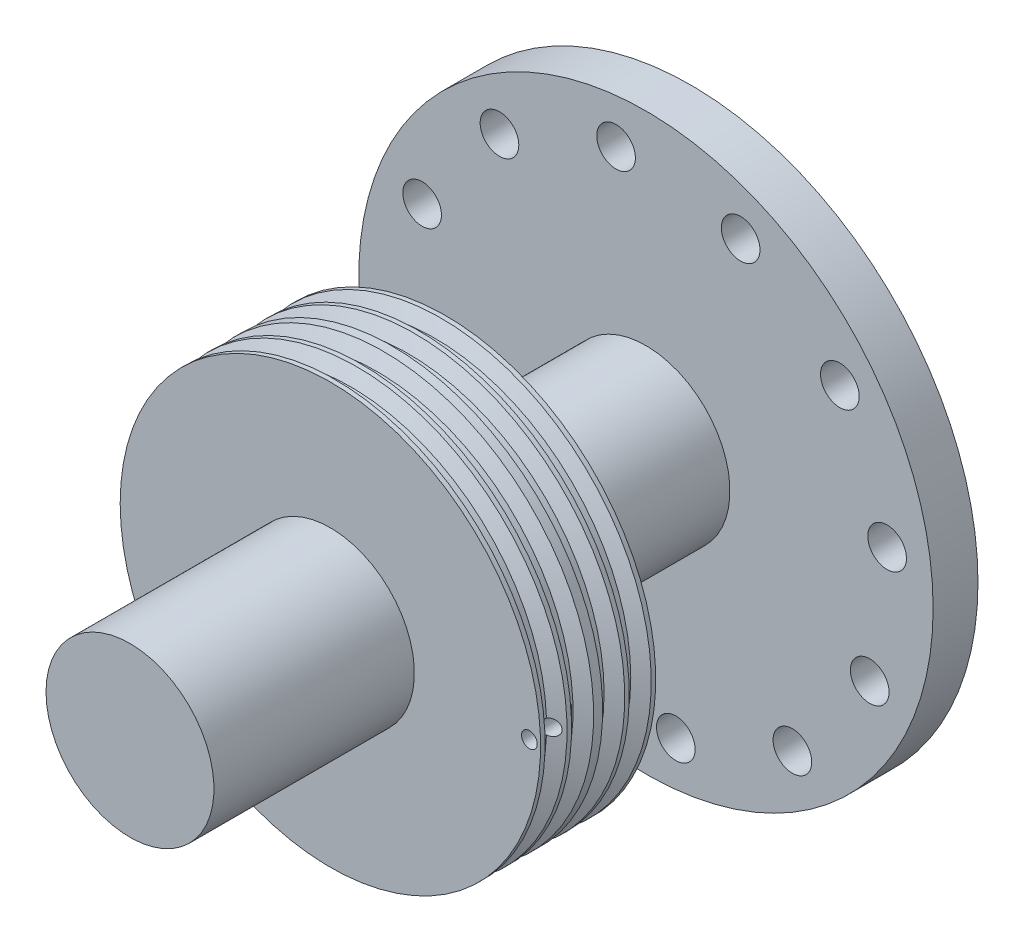
SolidWorks part; units mm, degrees
ref_plane "Front Plane" through (0, 0, 0) normal (0, 0, 1) x (1, 0, 0)
ref_plane "Top Plane" through (0, 0, 0) normal (0, 1, 0) x (1, 0, 0)
ref_plane "Right Plane" through (0, 0, 0) normal (1, 0, 0) x (0, 0, -1)
sketch "Sketch1" plane through (0, 0, 0) normal (0, 0, 1) x (1, 0, 0)
  circle A30 centre (0, 0) radius 25.6087
  arc A31 (-18.5962, 7.3851) -> (-21.3151, 9.5045) centre (-19.9557, 8.4448) ccw
  arc A32 (-21.3151, 9.5045) -> (-18.5962, 7.3851) centre (-19.9557, 8.4448) ccw
  arc A33 (-20.1451, -3.7241) -> (-22.8639, -1.6047) centre (-21.5045, -2.6644) ccw
  arc A34 (-22.8639, -1.6047) -> (-20.1451, -3.7241) centre (-21.5045, -2.6644) ccw
  arc A35 (-15.9318, -14.1194) -> (-18.6507, -12) centre (-17.2912, -13.0597) ccw
  arc A36 (-18.6507, -12) -> (-15.9318, -14.1194) centre (-17.2912, -13.0597) ccw
  arc A37 (-7.0854, -21.0154) -> (-9.8042, -18.896) centre (-8.4448, -19.9557) ccw
  arc A38 (-9.8042, -18.896) -> (-7.0854, -21.0154) centre (-8.4448, -19.9557) ccw
  arc A39 (4.0238, -22.5642) -> (1.305, -20.4448) centre (2.6644, -21.5045) ccw
  arc A40 (1.305, -20.4448) -> (4.0238, -22.5642) centre (2.6644, -21.5045) ccw
  arc A41 (11.7003, -16.2315) -> (14.4191, -18.3509) centre (13.0597, -17.2912) ccw
  arc A42 (14.4191, -18.3509) -> (11.7003, -16.2315) centre (13.0597, -17.2912) ccw
  arc A43 (18.5962, -7.3851) -> (21.3151, -9.5045) centre (19.9557, -8.4448) ccw
  arc A44 (21.3151, -9.5045) -> (18.5962, -7.3851) centre (19.9557, -8.4448) ccw
  arc A45 (22.8639, 1.6047) -> (20.1451, 3.7241) centre (21.5045, 2.6644) ccw
  arc A46 (20.1451, 3.7241) -> (22.8639, 1.6047) centre (21.5045, 2.6644) ccw
  arc A47 (15.9318, 14.1194) -> (18.6507, 12) centre (17.2912, 13.0597) ccw
  arc A48 (18.6507, 12) -> (15.9318, 14.1194) centre (17.2912, 13.0597) ccw
  arc A49 (7.0854, 21.0154) -> (9.8042, 18.896) centre (8.4448, 19.9557) ccw
  arc A50 (9.8042, 18.896) -> (7.0854, 21.0154) centre (8.4448, 19.9557) ccw
  arc A51 (-4.0238, 22.5642) -> (-1.305, 20.4448) centre (-2.6644, 21.5045) ccw
  arc A52 (-1.305, 20.4448) -> (-4.0238, 22.5642) centre (-2.6644, 21.5045) ccw
  arc A53 (-14.4191, 18.3509) -> (-11.7003, 16.2315) centre (-13.0597, 17.2912) ccw
  arc A54 (-11.7003, 16.2315) -> (-14.4191, 18.3509) centre (-13.0597, 17.2912) ccw
extrude "Boss-Extrude3" add sketch "Sketch1" along normal blind 4
sketch "Sketch9" plane through (0, 0, 0) normal (1, 0, 0) x (0, 0, -1)
  line L0 (0, 0) -> (-60.0062, 0) construction
  line L2 (-60.0062, 7.4874) -> (0, 7.4874)
  line L7 (0, 0) -> (-60.0062, 0)
  line L8 (0, 0) -> (0, 7.4874)
  line L10 (-60.0062, 0) -> (-60.0062, 7.4874)
  line L11 (-4, 7.4874) -> (-4, 0) construction
  line L12 (-4, 25.6087) -> (-4, -25.6087) construction
  line L13 (-60.0062, 3.7437) -> (-50.0062, 3.7437) construction
  line L14 (-50.0062, 7.4874) -> (-50.0062, 0)
  line L15 (-4, 7.4874) -> (-4, 0)
  line L16 (-50.0062, 3.7437) -> (-4, 3.7437) construction
  line L17 (-27.0031, 3.7437) -> (-27.0031, 18.7437) construction
  line L18 (-27.0031, 18.7437) -> (-37.0031, 18.7437) construction
  line L19 (-26.6031, 18.7437) -> (-27.4031, 18.7437)
  line L20 (-27.4031, 18.7437) -> (-27.989, 17.4872)
  line L21 (-27.989, 17.4872) -> (-28.789, 17.4872)
  line L22 (-28.789, 17.4872) -> (-29.3749, 18.7437)
  line L23 (-29.3749, 18.7437) -> (-29.7749, 18.7437)
  line L24 (-29.7749, 18.7437) -> (-30.3555, 17.4985)
  line L25 (-30.3555, 17.4985) -> (-31.1555, 17.4985)
  line L26 (-31.1555, 17.4985) -> (-31.7362, 18.7437)
  line L27 (-31.7362, 18.7437) -> (-32.1362, 18.7437)
  line L28 (-30.3555, 17.4985) -> (-30.3555, 19.923) construction
  line L29 (-31.1555, 17.4985) -> (-31.1555, 19.923) construction
  line L30 (-32.1362, 18.7437) -> (-32.1362, 7.4874)
  line L31 (-32.1362, 7.4874) -> (-21.87, 7.4874)
  line L32 (-27.0031, 7.4874) -> (-27.0031, 18.7437)
  line L33 (-21.87, 18.7437) -> (-21.87, 7.4874)
  line L34 (-22.27, 18.7437) -> (-21.87, 18.7437)
  line L35 (-22.8507, 17.4985) -> (-22.27, 18.7437)
  line L36 (-23.6507, 17.4985) -> (-22.8507, 17.4985)
  line L37 (-24.2313, 18.7437) -> (-23.6507, 17.4985)
  line L38 (-24.6313, 18.7437) -> (-24.2313, 18.7437)
  line L39 (-25.2172, 17.4872) -> (-24.6313, 18.7437)
  line L40 (-26.0172, 17.4872) -> (-25.2172, 17.4872)
  line L41 (-26.6031, 18.7437) -> (-26.0172, 17.4872)
  dimension "D1" = 10
  dimension "D2" = 15
  dimension "D3" = 25
  dimension "D4" = 25
  dimension "D5" = 0.8
  dimension "D6" = 0.4
  dimension "D7" = 0.4
  dimension "D8" = 0.4
  dimension "D9" = 21.87
revolve "Revolve1" add sketch "Sketch9" angle 360 about L7
sketch "Sketch10" plane through (0, 0, 32.1362) normal (0, 0, 1) x (1, 0, 0)
  line L0 (18.7437, 0) -> (17.7437, 0) construction
  circle A3 centre (17.7437, 0) radius 0.7
  circle A6 centre (0, 0) radius 18.7437 construction
  dimension "D1" = 1.4
  dimension "D2" = 1
extrude "Cut-Extrude1" cut sketch "Sketch10" against normal blind 4
sketch "Sketch11" plane through (0, 0, 21.87) normal (0, 0, -1) x (-1, 0, 0)
  line L0 (18.7437, 0) -> (17.7437, 0) construction
  circle A0 centre (0, 0) radius 18.7437 construction
  circle A1 centre (17.7437, 0) radius 0.7
  dimension "D1" = 1
extrude "Cut-Extrude2" cut sketch "Sketch11" against normal blind 4
